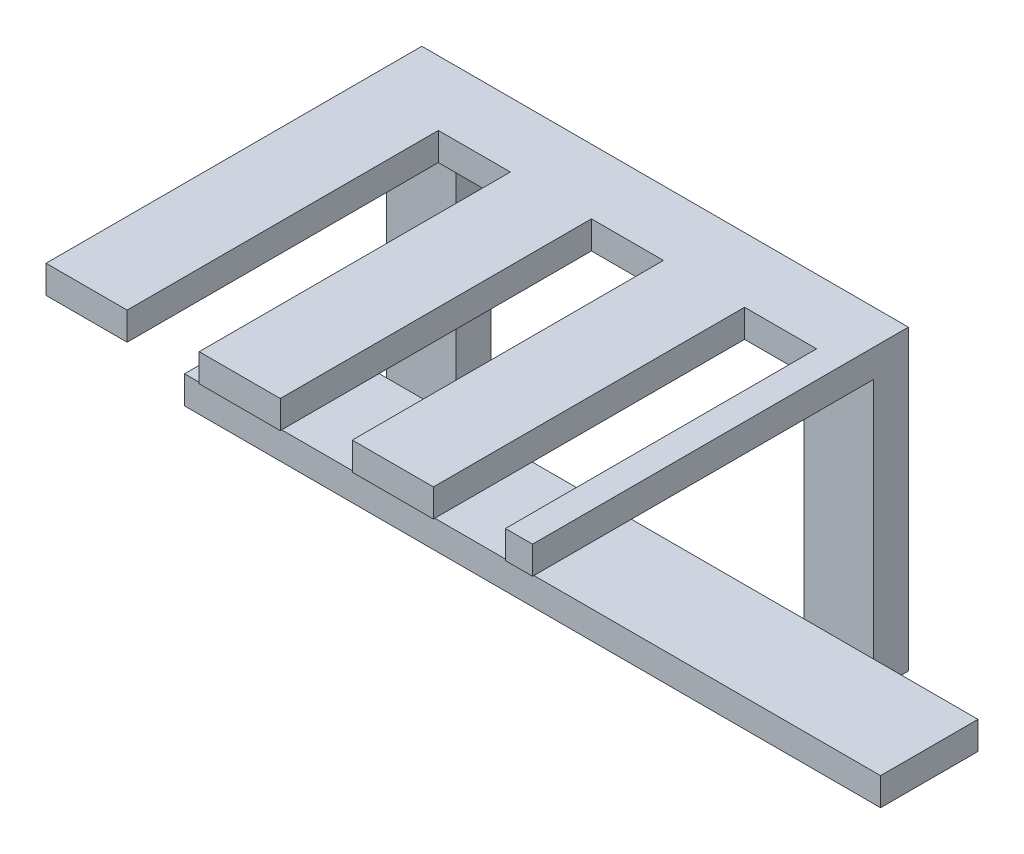
SolidWorks part; units mm, degrees
ref_plane "Front Plane" through (0, 0, 0) normal (0, 0, 1) x (1, 0, 0)
ref_plane "Top Plane" through (0, 0, 0) normal (0, 1, 0) x (1, 0, 0)
ref_plane "Right Plane" through (0, 0, 0) normal (1, 0, 0) x (0, 0, -1)
sketch "Sketch2" plane through (0, 0, 0) normal (0, 1, 0) x (1, 0, 0)
  line L1 (-50, 7) -> (50, 7)
  line L2 (-50, 7) -> (-50, -7)
  line L3 (-50, -7) -> (50, -7)
  line L4 (50, 7) -> (50, -7)
  line L5 (-50, 7) -> (50, -7) construction
  line L6 (-50, -7) -> (50, 7) construction
  point P0 (0, 0)
  dimension "D1" = 100
  dimension "D2" = 14
extrude "Boss-Extrude1" add sketch "Sketch2" along normal blind 4
sketch "Sketch3" plane through (0, 0, -7) normal (0, 0, -1) x (-1, 0, 0)
  line L0 (-50, 4) -> (50, 4) construction
  line L1 (-35, 4) -> (-25, 4)
  line L2 (-35, 4) -> (-35, 0)
  line L3 (-35, 0) -> (-25, 0)
  line L4 (-25, 4) -> (-25, 0)
  line L5 (-50, 0) -> (50, 0) construction
  line L7 (25, 4) -> (35, 4)
  line L8 (25, 4) -> (25, 0)
  line L9 (25, 0) -> (35, 0)
  line L10 (35, 4) -> (35, 0)
  dimension "D1" = 10
  dimension "D2" = 10
  dimension "D3" = 25
  dimension "D4" = 25
extrude "Boss-Extrude2" add sketch "Sketch3" along normal blind 5
sketch "Sketch4" plane through (0, 4, 0) normal (0, 1, 0) x (1, 0, 0)
  line L1 (-35, 7) -> (-25, 7)
  line L2 (-35, 7) -> (-35, 12)
  line L3 (-35, 12) -> (-25, 12)
  line L4 (-25, 7) -> (-25, 12)
  line L5 (25, 7) -> (35, 7)
  line L6 (25, 7) -> (25, 12)
  line L7 (25, 12) -> (35, 12)
  line L8 (35, 7) -> (35, 12)
extrude "Boss-Extrude3" add sketch "Sketch4" along normal blind 34.8
sketch "Sketch5" plane through (0, 0, -12) normal (0, 0, -1) x (-1, 0, 0)
  line L1 (-35, 38.8) -> (34.9046, 38.8)
  line L2 (-35, 38.8) -> (-35, 42.8)
  line L3 (-35, 42.8) -> (34.9046, 42.8)
  line L4 (34.9046, 38.8) -> (34.9046, 42.8)
  dimension "D1" = 4
extrude "Boss-Extrude4" add sketch "Sketch5" against normal blind 54
sketch "Sketch6" plane through (0, 42.8, 0) normal (0, 1, 0) x (1, 0, 0)
  line L6 (-34.9046, -42) -> (35, -42) construction
  line L7 (-23.2454, -42) -> (-12.8979, -42)
  line L8 (-23.2454, -42) -> (-23.2454, 2.7073)
  line L9 (-23.2454, 2.7073) -> (-12.8979, 2.7073)
  line L10 (-12.8979, -42) -> (-12.8979, 2.7073)
  line L11 (-1.2454, -42) -> (-1.2454, 2.7073)
  line L12 (-1.2454, -42) -> (9.1021, -42)
  line L13 (9.1021, -42) -> (9.1021, 2.7073)
  line L14 (-1.2454, 2.7073) -> (9.1021, 2.7073)
  line L15 (20.7546, -42) -> (20.7546, 2.7073)
  line L16 (20.7546, -42) -> (31.1021, -42)
  line L17 (31.1021, -42) -> (31.1021, 2.7073)
  line L18 (20.7546, 2.7073) -> (31.1021, 2.7073)
  dimension "D1" = 3
extrude "Cut-Extrude1" cut sketch "Sketch6" against normal blind 14
